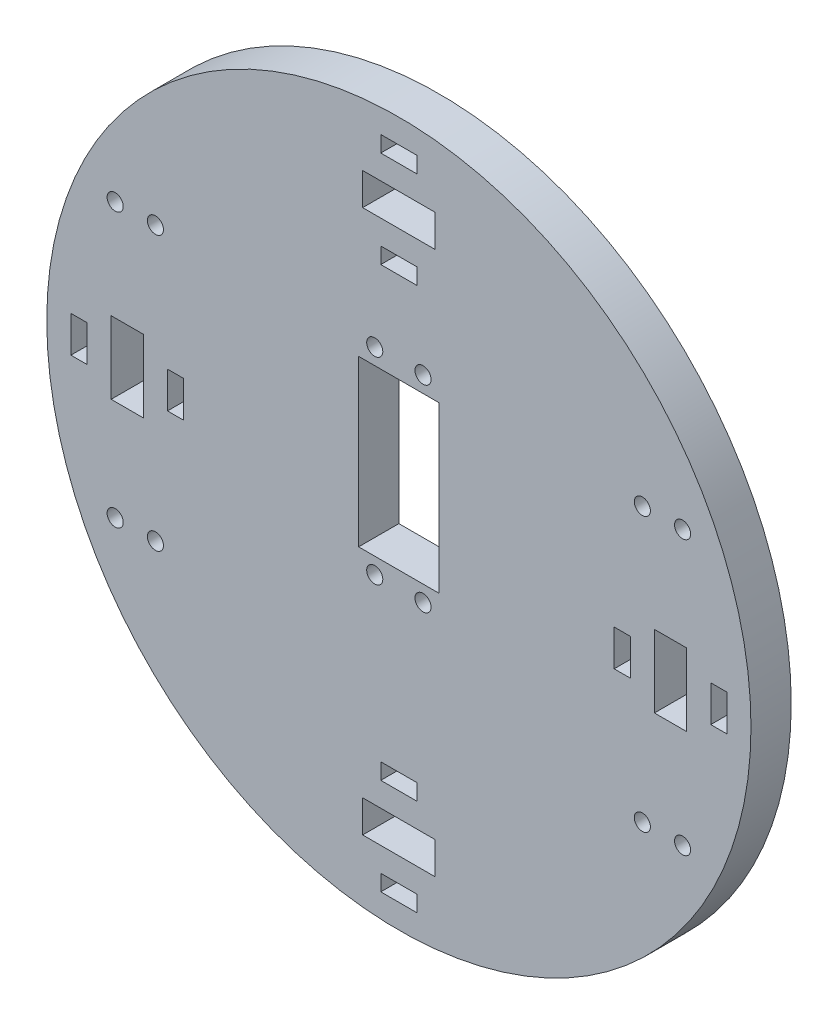
SolidWorks part; units mm, degrees
ref_plane "Front Plane" through (0, 0, 0) normal (0, 0, 1) x (1, 0, 0)
ref_plane "Top Plane" through (0, 0, 0) normal (0, 1, 0) x (1, 0, 0)
ref_plane "Right Plane" through (0, 0, 0) normal (1, 0, 0) x (0, 0, -1)
sketch "Sketch1" plane through (0, 0, 0) normal (0, 0, 1) x (1, 0, 0)
  line L0 (23.9434, 85.9678) -> (51.9434, 85.9678) construction
  line L1 (-61.0566, 91.9678) -> (23.9434, 91.9678) construction
  line L2 (-61.0566, 91.9678) -> (-61.0566, 11.9678) construction
  line L3 (-61.0566, 11.9678) -> (23.9434, 11.9678) construction
  line L4 (23.9434, 91.9678) -> (23.9434, 11.9678) construction
  line L5 (-61.0566, 91.9678) -> (23.9434, 11.9678) construction
  line L6 (-61.0566, 11.9678) -> (23.9434, 91.9678) construction
  line L7 (-8.5566, 82.9678) -> (-8.5566, 80.9226) construction
  line L8 (-28.5566, 82.9678) -> (-8.5566, 82.9678)
  line L9 (-28.5566, 82.9678) -> (-28.5566, 41.9678)
  line L10 (-18.5566, 91.9678) -> (-18.5566, 11.9678) construction
  line L11 (-61.0566, 51.9678) -> (23.9434, 51.9678) construction
  line L12 (-28.5566, 41.9678) -> (-8.5566, 41.9678)
  line L13 (-8.5566, 82.9678) -> (-8.5566, 41.9678)
  line L14 (-18.5566, 82.9678) -> (-18.5566, 41.9678) construction
  line L15 (-28.5566, 62.4678) -> (-8.5566, 62.4678) construction
  line L16 (-28.5566, 51.9678) -> (-8.5566, 51.9678) construction
  line L17 (-18.5566, 139.4678) -> (-18.5566, -35.5322) construction
  line L18 (68.9434, 51.9678) -> (-106.0566, 51.9678) construction
  line L19 (-27.5566, -11.5322) -> (-9.5566, -11.5322)
  line L20 (-27.5566, 123.4678) -> (-9.5566, 123.4678)
  line L21 (-27.5566, 123.4678) -> (-27.5566, 115.4678)
  line L22 (-27.5566, 115.4678) -> (-9.5566, 115.4678)
  line L23 (-9.5566, 123.4678) -> (-9.5566, 115.4678)
  line L24 (-27.5566, 123.4678) -> (-9.5566, 115.4678) construction
  line L25 (-27.5566, 115.4678) -> (-9.5566, 123.4678) construction
  line L26 (-9.5566, -19.5322) -> (-9.5566, -11.5322)
  line L27 (-27.5566, -19.5322) -> (-9.5566, -19.5322)
  line L28 (-27.5566, -19.5322) -> (-27.5566, -11.5322)
  line L29 (-82.0566, 42.9678) -> (-90.0566, 42.9678)
  line L30 (44.9434, 60.9678) -> (52.9434, 60.9678)
  line L31 (44.9434, 60.9678) -> (44.9434, 42.9678)
  line L32 (44.9434, 42.9678) -> (52.9434, 42.9678)
  line L33 (52.9434, 60.9678) -> (52.9434, 42.9678)
  line L34 (44.9434, 60.9678) -> (52.9434, 42.9678) construction
  line L35 (44.9434, 42.9678) -> (52.9434, 60.9678) construction
  line L36 (-82.0566, 60.9678) -> (-82.0566, 42.9678)
  line L37 (-90.0566, 60.9678) -> (-90.0566, 42.9678)
  line L38 (-82.0566, 60.9678) -> (-90.0566, 60.9678)
  line L39 (-27.5566, 119.4678) -> (-9.5566, 119.4678) construction
  line L40 (-23.0566, 133.4678) -> (-14.0566, 133.4678)
  line L41 (-23.0566, 133.4678) -> (-23.0566, 129.4678)
  line L42 (-23.0566, 129.4678) -> (-14.0566, 129.4678)
  line L43 (-14.0566, 133.4678) -> (-14.0566, 129.4678)
  line L44 (-23.0566, 133.4678) -> (-14.0566, 129.4678) construction
  line L45 (-23.0566, 129.4678) -> (-14.0566, 133.4678) construction
  line L46 (-14.0566, 105.4678) -> (-14.0566, 109.4678)
  line L47 (-23.0566, 109.4678) -> (-14.0566, 109.4678)
  line L48 (-23.0566, 105.4678) -> (-23.0566, 109.4678)
  line L49 (-23.0566, 105.4678) -> (-14.0566, 105.4678)
  line L50 (-23.0566, -29.5322) -> (-23.0566, -25.5322)
  line L51 (-23.0566, -29.5322) -> (-14.0566, -29.5322)
  line L52 (-14.0566, -29.5322) -> (-14.0566, -25.5322)
  line L53 (-23.0566, -25.5322) -> (-14.0566, -25.5322)
  line L54 (-23.0566, -1.5322) -> (-23.0566, -5.5322)
  line L55 (-23.0566, -5.5322) -> (-14.0566, -5.5322)
  line L56 (-14.0566, -1.5322) -> (-14.0566, -5.5322)
  line L57 (-23.0566, -1.5322) -> (-14.0566, -1.5322)
  line L58 (48.9434, 60.9678) -> (48.9434, 42.9678) construction
  line L59 (58.9434, 56.4678) -> (62.9434, 56.4678)
  line L60 (58.9434, 56.4678) -> (58.9434, 47.4678)
  line L61 (58.9434, 47.4678) -> (62.9434, 47.4678)
  line L62 (62.9434, 56.4678) -> (62.9434, 47.4678)
  line L63 (58.9434, 56.4678) -> (62.9434, 47.4678) construction
  line L64 (58.9434, 47.4678) -> (62.9434, 56.4678) construction
  line L65 (38.9434, 47.4678) -> (34.9434, 47.4678)
  line L66 (38.9434, 56.4678) -> (38.9434, 47.4678)
  line L67 (34.9434, 56.4678) -> (34.9434, 47.4678)
  line L68 (38.9434, 56.4678) -> (34.9434, 56.4678)
  line L69 (-72.0566, 56.4678) -> (-72.0566, 47.4678)
  line L70 (-76.0566, 47.4678) -> (-72.0566, 47.4678)
  line L71 (-76.0566, 56.4678) -> (-76.0566, 47.4678)
  line L72 (-76.0566, 56.4678) -> (-72.0566, 56.4678)
  line L73 (-96.0566, 47.4678) -> (-100.0566, 47.4678)
  line L74 (-100.0566, 56.4678) -> (-100.0566, 47.4678)
  line L75 (-96.0566, 56.4678) -> (-96.0566, 47.4678)
  line L76 (-96.0566, 56.4678) -> (-100.0566, 56.4678)
  circle A0 centre (-18.5566, 51.9678) radius 87.5
  circle A1 centre (41.9434, 85.9678) radius 2
  circle A2 centre (51.9434, 85.9678) radius 2
  circle A3 centre (-12.5566, 86.9678) radius 2
  circle A4 centre (-24.5566, 86.9678) radius 2
  circle A5 centre (-12.5566, 37.9678) radius 2
  circle A6 centre (-24.5566, 37.9678) radius 2
  circle A7 centre (51.9434, 17.9678) radius 2
  circle A8 centre (41.9434, 17.9678) radius 2
  circle A9 centre (-89.0566, 85.9678) radius 2
  circle A10 centre (-79.0566, 85.9678) radius 2
  circle A11 centre (-79.0566, 17.9678) radius 2
  circle A12 centre (-89.0566, 17.9678) radius 2
  point P6 (-18.5566, 51.9678)
  point P14 (-18.5566, 51.9678)
  point P44 (-18.5566, 119.4678)
  point P65 (48.9434, 51.9678)
  point P74 (-18.5566, 131.4678)
  point P93 (60.9434, 51.9678)
  dimension "D1" = 175
  dimension "D5" = 4
  dimension "D7" = 4
  dimension "D11" = 4
  dimension "D14" = 31
  dimension "D21" = 9
  dimension "D2" = 85
  dimension "D3" = 80
  dimension "D4" = 6
  dimension "D6" = 18
  dimension "D8" = 10
  dimension "D9" = 41
  dimension "D10" = 20
  dimension "D12" = 4
  dimension "D13" = 4
  dimension "D15" = 8
  dimension "D16" = 18
  dimension "D17" = 20
  dimension "D18" = 8
  dimension "D19" = 18
  dimension "D20" = 20
  dimension "D22" = 4
  dimension "D23" = 12
  dimension "D24" = 4
  dimension "D25" = 9
  dimension "D26" = 12
extrude "Boss-Extrude2" add sketch "Sketch1" along normal blind 10
